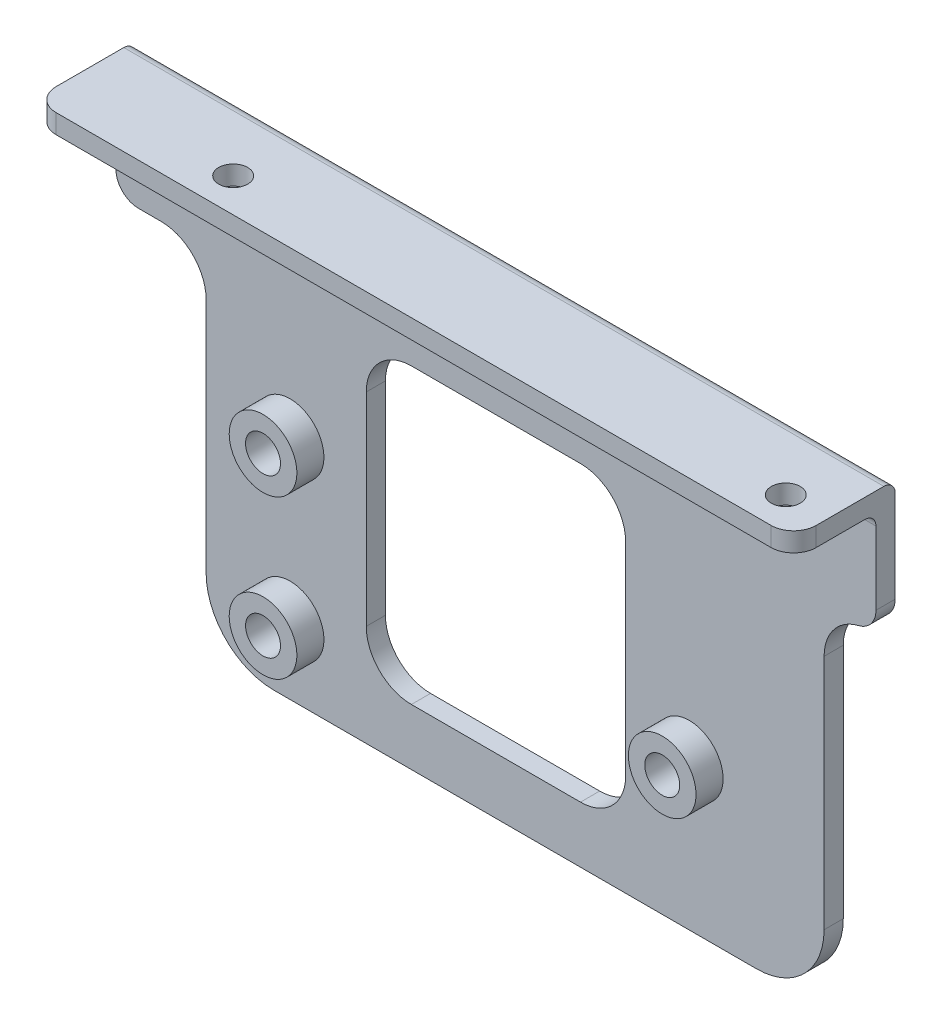
SolidWorks part; units mm, degrees
material "ABS"
ref_plane "Front Plane" through (0, 0, 0) normal (0, 0, 1) x (1, 0, 0)
ref_plane "Top Plane" through (0, 0, 0) normal (0, 1, 0) x (1, 0, 0)
ref_plane "Right Plane" through (0, 0, 0) normal (1, 0, 0) x (0, 0, -1)
sketch "Sketch1" plane through (0, 0, 0) normal (0, 0, 1) x (1, 0, 0)
  line L1 (42.799, 26.67) -> (-42.799, 26.67)
  line L2 (42.799, 26.67) -> (42.799, -26.67)
  line L3 (42.799, -26.67) -> (-42.799, -26.67)
  line L4 (-42.799, 26.67) -> (-42.799, -26.67)
  line L5 (42.799, 26.67) -> (-42.799, -26.67) construction
  line L6 (42.799, -26.67) -> (-42.799, 26.67) construction
  point P0 (0, 0)
  dimension "D1" = 85.598
  dimension "D2" = 53.34
extrude "Boss-Extrude1" add sketch "Sketch1" along normal blind 2.159
sketch "Sketch2" plane through (0, 0, 2.159) normal (0, 0, 1) x (1, 0, 0)
  line L0 (-42.799, 26.67) -> (-42.799, -26.67) construction
  line L1 (42.799, 26.67) -> (-42.799, 26.67)
  line L2 (42.799, 26.67) -> (42.799, 24.511)
  line L3 (42.799, 24.511) -> (-42.799, 24.511)
  line L4 (-42.799, 26.67) -> (-42.799, 24.511)
  dimension "D1" = 2.159
extrude "Boss-Extrude2" add sketch "Sketch2" along normal blind 9.271
fillet "Fillet1" radius 1.27 1 edges at (0, 24.511, 2.159)
fillet "Fillet2" radius 1.27 1 edges at (0, 26.67, 0)
fillet "Fillet3" radius 2.54 2 edges at (42.799, 25.5905, 11.43) (-42.799, 25.5905, 11.43)
sketch "Sketch3" plane through (0, 0, 2.159) normal (0, 0, 1) x (1, 0, 0)
  line L0 (-42.799, -26.67) -> (42.799, -26.67) construction
  line L1 (-14.605, -20.32) -> (14.605, -20.32)
  line L2 (-14.605, -20.32) -> (-14.605, 12.7)
  line L3 (-14.605, 12.7) -> (14.605, 12.7)
  line L4 (14.605, -20.32) -> (14.605, 12.7)
  line L5 (-42.799, 23.241) -> (-42.799, -26.67) construction
  dimension "D1" = 6.35
  dimension "D2" = 28.194
  dimension "D3" = 33.02
  dimension "D4" = 29.21
extrude "Cut-Extrude1" cut sketch "Sketch3" against normal through all
fillet "Fillet5" radius 5.08 4 edges at (14.605, -20.32, 1.0795) (-14.605, -20.32, 1.0795) (14.605, 12.7, 1.0795) (-14.605, 12.7, 1.0795)
hole_wizard "#4 Clearance Hole1" positions "Sketch4" profile "Sketch5" hole size "#4" standard "ANSI Inch" end condition through all
sketch "Sketch4" plane through (0, 24.511, 0) normal (0, -1, 0) x (-1, 0, 0)
  line L0 (-42.799, -8.89) -> (-42.799, -3.429) construction
  line L1 (40.259, -11.43) -> (-40.259, -11.43) construction
  point P0 (-38.1, -7.62)
  point P2 (24.13, -7.62)
  dimension "D1" = 62.23
  dimension "D2" = 4.699
  dimension "D3" = 3.81
sketch "Sketch5" plane through (38.1, 24.511, 7.62) normal (1, 0, 0) x (0, 0, -1)
  line L0 (0, 0) -> (0, 2.159)
  line L1 (0, 2.159) -> (1.6319, 2.159)
  line L2 (1.6319, 2.159) -> (1.6319, 0)
  line L5 (1.6319, 0) -> (0, 0)
  line L11 (0, -6.35) -> (0, 107.95) construction
  dimension "Thru Hole Dia." = 3.2639
  dimension "Thru Hole Depth" = 2.159
sketch "Sketch18" plane through (0, 0, 2.159) normal (0, 0, 1) x (1, 0, 0)
  line L0 (-23.1831, -1.143) -> (-23.1831, -18.923) construction
  line L1 (42.799, 23.241) -> (-42.799, 23.241) construction
  circle A0 centre (-23.1831, -1.143) radius 3.81
  circle A1 centre (-23.1831, -18.923) radius 3.81
  circle A2 centre (21.7749, -10.033) radius 3.81
  dimension "D1" = 7.62
  dimension "D2" = 17.78
  dimension "D3" = 44.958
  dimension "D4" = 24.384
  dimension "D5" = 8.89
extrude "Boss-Extrude6" add sketch "Sketch18" along normal blind 3.048
sketch "Sketch19" plane through (0, 0, 5.207) normal (0, 0, 1) x (1, 0, 0)
  circle A0 centre (-23.1831, -18.923) radius 1.9685
  circle A1 centre (21.7749, -10.033) radius 1.9685
  circle A2 centre (-23.1831, -1.143) radius 1.9685
  circle A3 centre (-23.1831, -1.143) radius 3.81 construction
  dimension "D1" = 3.937
extrude "Cut-Extrude7" cut sketch "Sketch19" against normal blind 3.429
sketch "Sketch20" plane through (0, 0, 1.778) normal (0, 0, 1) x (1, 0, 0)
  circle A0 centre (-23.1831, -1.143) radius 0.9525
  circle A1 centre (-23.1831, -18.923) radius 0.9525
  circle A2 centre (21.7749, -10.033) radius 0.9525
  dimension "D1" = 1.905
extrude "Cut-Extrude8" cut sketch "Sketch20" against normal through all
sketch "Sketch21" plane through (0, 0, 2.159) normal (0, 0, 1) x (1, 0, 0)
  line L0 (-42.799, 23.241) -> (-42.799, -26.67) construction
  line L1 (-42.799, 12.7) -> (-37.719, 12.7)
  line L2 (-42.799, 12.7) -> (-42.799, -26.67)
  line L3 (-42.799, -26.67) -> (-32.639, -26.67)
  line L4 (-32.639, 7.62) -> (-32.639, -26.67)
  line L5 (-42.799, -26.67) -> (42.799, -26.67) construction
  arc A0 (-32.639, 7.62) -> (-37.719, 12.7) centre (-37.719, 7.62) ccw
  point P10 (-32.639, 12.7)
  dimension "D3" = 5.08
  dimension "D1" = 10.16
  dimension "D2" = 39.37
extrude "Cut-Extrude9" cut sketch "Sketch21" against normal through all
fillet "Fillet6" radius 2.54 1 edges at (-42.799, 12.7, 1.0795)
fillet "Fillet7" radius 7.62 1 edges at (-32.639, -26.67, 1.0795)
sketch "Sketch22" plane through (0, 0, 2.159) normal (0, 0, 1) x (1, 0, 0)
  line L0 (42.799, -26.67) -> (42.799, 23.241) construction
  line L1 (42.799, 12.7) -> (42.037, 12.7)
  line L2 (42.799, 12.7) -> (42.799, -26.67)
  line L3 (42.799, -26.67) -> (36.957, -26.67)
  line L4 (36.957, 7.62) -> (36.957, -26.67)
  line L5 (-25.019, -26.67) -> (42.799, -26.67) construction
  arc A2 (36.957, 7.62) -> (42.037, 12.7) centre (42.037, 7.62) cw
  dimension "D2" = 39.37
  dimension "D3" = 5.08
  dimension "D1" = 5.842
extrude "Cut-Extrude10" cut sketch "Sketch22" against normal through all
fillet "Fillet8" radius 2.54 1 edges at (42.799, 12.7, 1.0795)
fillet "Fillet9" radius 7.62 1 edges at (36.957, -26.67, 1.0795)
